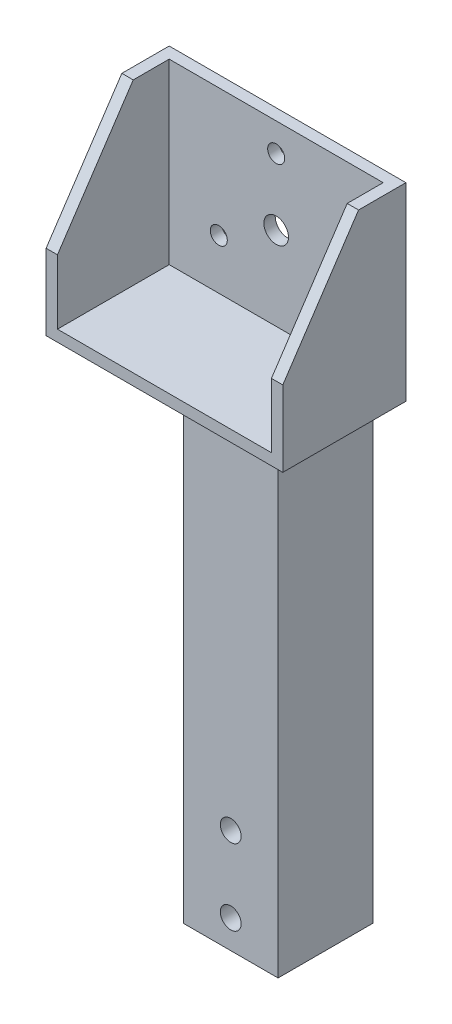
SolidWorks part; units mm, degrees
material "普通碳钢"
ref_plane "前视基准面" through (0, 0, 0) normal (0, 0, 1) x (1, 0, 0)
ref_plane "上视基准面" through (0, 0, 0) normal (0, 1, 0) x (1, 0, 0)
ref_plane "右视基准面" through (0, 0, 0) normal (1, 0, 0) x (0, 0, -1)
sketch "草图1" plane through (0, 0, 0) normal (0, 0, 1) x (1, 0, 0)
  line L1 (0, 0) -> (125, 0)
  line L2 (0, 0) -> (0, 100)
  line L3 (0, 100) -> (125, 100)
  line L4 (125, 0) -> (125, 100)
  dimension "D1" = 100
  dimension "D2" = 125
extrude "凸台-拉伸1" add sketch "草图1" along normal blind 65
shell "抽壳1" thickness 6
sketch "草图2" plane through (125, 0, 0) normal (1, 0, 0) x (0, 0, -1)
  line L0 (-65, 100) -> (-25, 100)
  line L1 (-65, 100) -> (0, 100) construction
  line L2 (-25, 100) -> (-65, 40)
  line L3 (-65, 0) -> (-65, 100) construction
  line L4 (-65, 40) -> (-65, 100)
  dimension "D1" = 60
  dimension "D2" = 40
extrude "切除-拉伸1" cut sketch "草图2" against normal up to surface (125 mm away) up to face at (0, 50, 32.5)
sketch "草图3" plane through (0, 0, 0) normal (0, -1, 0) x (1, 0, 0)
  line L0 (0, 32.5) -> (125, 32.5) construction
  line L1 (65, 57.5) -> (115, 57.5)
  line L2 (65, 57.5) -> (65, 7.5)
  line L3 (65, 7.5) -> (115, 7.5)
  line L4 (115, 57.5) -> (115, 7.5)
  line L5 (0, 65) -> (0, 0) construction
  line L6 (125, 65) -> (125, 0) construction
  dimension "D1" = 50
  dimension "D2" = 50
  dimension "D3" = 25
  dimension "D4" = 60
extrude "凸台-拉伸2" add sketch "草图3" along normal blind 240
sketch "草图4" plane through (0, 0, 57.5) normal (0, 0, 1) x (1, 0, 0)
  line L0 (90, 0) -> (90, -240) construction
  line L1 (115, 0) -> (65, 0) construction
  line L2 (115, -240) -> (65, -240) construction
  circle A0 centre (90, -225) radius 5.5
  circle A1 centre (90, -185) radius 5.5
  dimension "D1" = 11
  dimension "D2" = 11
  dimension "D3" = 15
  dimension "D4" = 40
extrude "切除-拉伸2" cut sketch "草图4" against normal blind 240
sketch "草图5" plane through (0, 0, 0) normal (0, 0, -1) x (-1, 0, 0)
  line L0 (-125, 50) -> (0, 50) construction
  line L1 (-125, 0) -> (-125, 100) construction
  line L2 (0, 100) -> (0, 0) construction
  line L3 (-62.5, 100) -> (-62.5, 0) construction
  line L4 (-125, 100) -> (0, 100) construction
  line L5 (0, 0) -> (-125, 0) construction
  circle A0 centre (-62.5, 50) radius 6.5
  dimension "D1" = 13
extrude "切除-拉伸5" cut sketch "草图5" against normal blind 240
sketch "草图6" plane through (0, 0, 0) normal (0, 0, -1) x (-1, 0, 0)
  line L0 (-62.5, 43.5) -> (-62.5, 100) construction
  line L1 (-125, 100) -> (0, 100) construction
  circle A0 centre (-62.5, 50) radius 6.5 construction
  circle A1 centre (-62.5, 85) radius 4.5
  dimension "D1" = 9
  dimension "D2" = 35
extrude "切除-拉伸6" cut sketch "草图6" against normal blind 240
pattern_circular "阵列(圆周)1" count 3 over 360 about axis through (62.5, 50, 0) along (0, 0, 1) of "切除-拉伸6"
